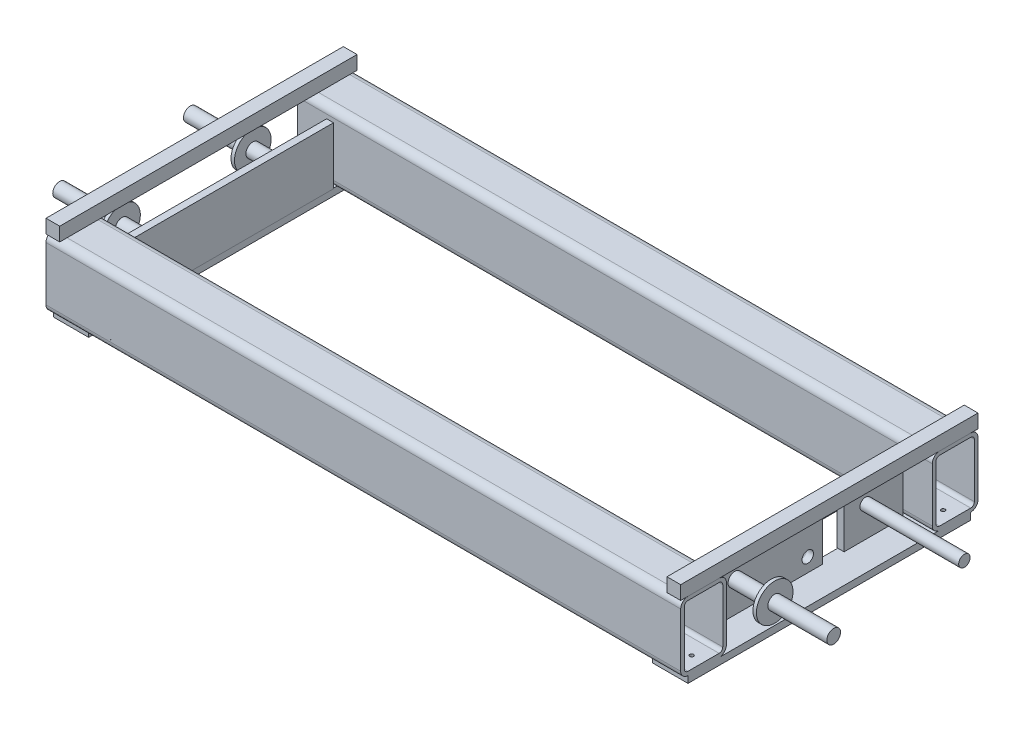
SolidWorks part; units mm, degrees
material "Plain Carbon Steel"
ref_plane "Front Plane" through (0, 0, 0) normal (0, 0, 1) x (1, 0, 0)
ref_plane "Top Plane" through (0, 0, 0) normal (0, 1, 0) x (1, 0, 0)
ref_plane "Right Plane" through (0, 0, 0) normal (1, 0, 0) x (0, 0, -1)
sketch "Sketch2" plane through (0, 0, 0) normal (0, 1, 0) x (1, 0, 0)
  line L0 (-277.5, 110) -> (-277.5, -110) construction
  line L3 (-277.5, -110) -> (277.5, -110)
  line L5 (-277.5, 110) -> (277.5, 110)
  line L6 (277.5, -110) -> (277.5, 110) construction
  line L7 (0, 110) -> (0, -110) construction
  line L8 (-277.5, 0) -> (277.5, 0) construction
  point P4 (0, 0)
  dimension "D1" = 220
  dimension "D3" = 220
  dimension "D4" = 555
other " C:\\PROGRAM FILES\\SOLIDWORKS CORP\\SOLIDWORKS\\LANG\\ENGLISH\\WELDMENT PROFILES\\BSI\\TUBE RECTANGULAR - IS MISSING(1)"
ref_plane "Plane1" through (-277.5, 0, 110) normal (1, 0, 0) x (0, 0, -1)
sketch "Sketch1" plane through (-277.5, 0, 110) normal (1, 0, 0) x (0, 0, -1)
  line L0 (-13.6, -26.8) -> (13.6, -26.8)
  line L1 (-16.8, -23.6) -> (-16.8, 23.6)
  line L2 (13.6, 26.8) -> (-13.6, 26.8)
  line L3 (16.8, 23.6) -> (16.8, -23.6)
  line L4 (-13.6, -30) -> (13.6, -30)
  line L5 (-20, -23.6) -> (-20, 23.6)
  line L6 (13.6, 30) -> (-13.6, 30)
  line L7 (20, 23.6) -> (20, -23.6)
  line L8 (-20, 0) -> (-16.8, 0) construction
  line L9 (-16.8, 0) -> (16.8, 0) construction
  line L10 (16.8, 0) -> (20, 0) construction
  line L11 (0, 30) -> (0, 26.8) construction
  line L12 (0, 26.8) -> (0, -26.8) construction
  line L13 (0, -26.8) -> (0, -30) construction
  arc A0 (20, 23.6) -> (13.6, 30) centre (13.6, 23.6) ccw
  arc A1 (13.6, -30) -> (20, -23.6) centre (13.6, -23.6) ccw
  arc A2 (-20, -23.6) -> (-13.6, -30) centre (-13.6, -23.6) ccw
  arc A3 (-13.6, 30) -> (-20, 23.6) centre (-13.6, 23.6) ccw
  arc A4 (-13.6, 26.8) -> (-16.8, 23.6) centre (-13.6, 23.6) ccw
  arc A5 (16.8, 23.6) -> (13.6, 26.8) centre (13.6, 23.6) ccw
  arc A6 (13.6, -26.8) -> (16.8, -23.6) centre (13.6, -23.6) ccw
  arc A7 (-16.8, -23.6) -> (-13.6, -26.8) centre (-13.6, -23.6) ccw
  point P6 (20, -30)
  point P33 (-20, -30)
  point P35 (-20, 30)
  point P36 (20, 30)
  point P37 (0, 0)
  point P38 (0, 0)
  dimension "D1" = 6.4
  dimension "Thickness" = 3.2
  dimension "V_leg" = 60
  dimension "H_leg" = 40
sketch "Sketch3" plane through (0, 30, 0) normal (0, 1, 0) x (1, 0, 0)
  line L0 (277.5, 130) -> (-277.5, 130) construction
  line L1 (-277.5, -130) -> (-265.5, -130)
  line L2 (-277.5, -130) -> (-277.5, 130)
  line L3 (-277.5, 130) -> (-265.5, 130)
  line L4 (-265.5, -130) -> (-265.5, 130)
  line L5 (0, 178.4485) -> (0, -196.2826) construction
  line L6 (265.5, -130) -> (265.5, 130)
  line L7 (277.5, 130) -> (265.5, 130)
  line L8 (277.5, -130) -> (277.5, 130)
  line L9 (277.5, -130) -> (265.5, -130)
  dimension "D2" = 12
extrude "Boss-Extrude1" add sketch "Sketch3" along normal blind 12 separate body
sketch "Sketch4" plane through (0, 0, 0) normal (0, 0, 1) x (1, 0, 0)
  line L0 (277.5, -30) -> (-277.5, -30) construction
  line L1 (-252.1, -30) -> (-246.1, -30)
  line L2 (-252.1, -30) -> (-252.1, 20)
  line L3 (-252.1, 20) -> (-246.1, 20)
  line L4 (-246.1, -30) -> (-246.1, 20)
  line L5 (-277.5, 23.6) -> (-277.5, -23.6) construction
  line L6 (0, 63.6899) -> (0, -88.2201) construction
  line L7 (246.1, -30) -> (246.1, 20)
  line L8 (252.1, 20) -> (246.1, 20)
  line L9 (252.1, -30) -> (252.1, 20)
  line L10 (252.1, -30) -> (246.1, -30)
  dimension "D1" = 50
  dimension "D2" = 6
  dimension "D3" = 25.4
  dimension "D4" = 151.9099
extrude "Boss-Extrude2" add sketch "Sketch4" along normal mid plane 180 separate body
sketch "Sketch5" plane through (-252.1, 0, 0) normal (-1, 0, 0) x (0, 0, 1)
  line L0 (90, -30) -> (-90, -30) construction
  line L1 (0, 51.6553) -> (0, -66.7942) construction
  circle A0 centre (-57.15, -3) radius 6
  circle A1 centre (57.15, -3) radius 6
  dimension "D1" = 12
  dimension "D2" = 27
  dimension "D4" = 114.3
  dimension "D3" = 118.4495
extrude "Boss-Extrude3" add sketch "Sketch5" along normal blind 86.36 separate body contours A0
sketch "Sketch7" plane through (-338.46, 0, 0) normal (-1, 0, 0) x (0, 0, 1)
  circle A0 centre (-57.15, -3) radius 16
  circle A1 centre (57.15, -3) radius 16
  circle A2 centre (57.15, -3) radius 6 construction
  circle A3 centre (-57.15, -3) radius 6 construction
  circle A4 centre (57.15, -3) radius 6
  circle A5 centre (-57.15, -3) radius 6
  dimension "D2" = 32
extrude "Boss-Extrude4" add sketch "Sketch7" along normal blind 3 from offset 54.61 separate body offset against normal yes
sketch "Sketch8" plane through (252.1, 0, 0) normal (1, 0, 0) x (0, 0, -1)
  circle A0 centre (-57.15, -3) radius 6
  circle A1 centre (57.15, -3) radius 5
  dimension "D1" = 12
  dimension "D2" = 10
extrude "Boss-Extrude5" add sketch "Sketch8" along normal blind 86.36 separate body
sketch "Sketch9" plane through (338.46, 0, 0) normal (1, 0, 0) x (0, 0, -1)
  circle A0 centre (-57.15, -3) radius 6 construction
  circle A1 centre (-57.15, -3) radius 6
  circle A2 centre (-57.15, -3) radius 16
  dimension "D1" = 32
extrude "Boss-Extrude6" add sketch "Sketch9" along normal blind 3 from offset 54.61 separate body offset against normal yes
sketch "Sketch10" plane through (0, -30, 0) normal (0, -1, 0) x (1, 0, 0)
  line L1 (-277.5, -123.6) -> (-246.5618, -123.6)
  line L2 (-277.5, -123.6) -> (-277.5, 123.6)
  line L3 (-277.5, 123.6) -> (-246.5618, 123.6)
  line L4 (-246.5618, -123.6) -> (-246.5618, 123.6)
  line L5 (277.5, 123.6) -> (-277.5, 123.6) construction
extrude "Boss-Extrude7" add sketch "Sketch10" along normal blind 6 separate body
sketch "Sketch11" plane through (0, -36, 0) normal (0, -1, 0) x (1, 0, 0)
  line L0 (-277.5, -110) -> (277.5, -110) construction
  line L1 (-246.5618, -123.6) -> (-246.5618, 123.6) construction
  line L2 (-277.5, 123.6) -> (-277.5, -123.6) construction
  line L3 (305.25, 0) -> (-305.25, 0) construction
  circle A0 centre (-256.8912, -110) radius 1.65
  circle A1 centre (-267.086, -110) radius 1.65
  circle A2 centre (-267.086, 110) radius 1.65
  circle A3 centre (-256.8912, 110) radius 1.65
  dimension "D1" = 3.3
  dimension "D2" = 3.3
  dimension "D3" = 10.3293
  dimension "D4" = 10.414
extrude "Cut-Extrude1" cut sketch "Sketch11" against normal up to surface (9.2 mm away)
mirror "Mirror1" about plane through (0, 0, 0) normal (1, 0, 0) of "Cut-Extrude1", "Boss-Extrude7"
sketch "Sketch12" plane through (0, 30, 0) normal (0, 1, 0) x (1, 0, 0)
  line L0 (277.5, 64.209) -> (277.5, -114.5446) construction
  line L1 (277.5, -110) -> (277.5, 110) construction
  line L2 (277.5, -130) -> (277.5, 130) construction
  line L3 (283.85, -41.15) -> (283.85, -73.15) construction
  line L4 (252.1, 90) -> (252.1, -90) construction
  dimension "D1" = 6.35
ref_plane "Plane4" through (0, 0, -19.23) normal (0, 0, 1) x (1, 0, 0)
sketch "Sketch18" plane through (0, 0, -19.23) normal (0, 0, 1) x (1, 0, 0)
  line L0 (252.1, 2) -> (252.1, -8) construction
  circle A0 centre (238.004, -3) radius 5
  dimension "D1" = 10
  dimension "D2" = 14.096
extrude "Extrude-Thin1" add sketch "Sketch18" along normal blind 25.4 separate body thin
sketch "Sketch19" plane through (0, 0, -19.23) normal (0, 0, -1) x (-1, 0, 0)
  circle A0 centre (-238.004, -3) radius 5
extrude "Boss-Extrude8" add sketch "Sketch19" along normal blind 131.73 from surface at -25.4 separate body starting at face at (246.004, -3, 6.17)
sketch "Sketch20" plane through (246.1, 0, 0) normal (-1, 0, 0) x (0, 0, 1)
  line L1 (-12.88, 17.7) -> (-0.18, 17.7)
  line L2 (-12.88, 17.7) -> (-12.88, -23.7)
  line L3 (-12.88, -23.7) -> (-0.18, -23.7)
  line L4 (-0.18, 17.7) -> (-0.18, -23.7)
  line L6 (-6.53, 17.7) -> (-6.53, -27.7526) construction
  line L7 (-19.23, 5) -> (-19.23, -11) construction
  line L8 (6.17, 5) -> (-19.23, 5) construction
  line L9 (-19.23, -11) -> (6.17, -11) construction
  dimension "D1" = 12.7
  dimension "D2" = 12.7
  dimension "D3" = 12.7
  dimension "D4" = 6.35
  dimension "D5" = 12.7
  dimension "D6" = 41.4
extrude "Boss-Extrude9" add sketch "Sketch20" along normal blind 3 separate body
sketch "Sketch21" plane through (243.1, 0, 0) normal (-1, 0, 0) x (0, 0, 1)
  line L0 (-12.88, 17.7) -> (-12.88, -23.7) construction
  circle A0 centre (-6.53, 10.8151) radius 5
  circle A1 centre (-6.53, -17.8621) radius 5
  dimension "D1" = 10
  dimension "D2" = 10
  dimension "D3" = 6.35
extrude "Cut-Extrude2" cut sketch "Sketch21" against normal up to surface (9 mm away)
sketch "Sketch22" plane through (246.1, 0, 0) normal (-1, 0, 0) x (0, 0, 1)
  line L0 (90, 20) -> (-90, 20) construction
  line L1 (-38.28, 20) -> (-19.23, 20)
  line L2 (-38.28, 20) -> (-38.28, -30)
  line L3 (-38.28, -30) -> (-19.23, -30)
  line L4 (-19.23, 20) -> (-19.23, -30)
  line L5 (90, -30) -> (-90, -30) construction
  line L6 (-19.23, -25.96) -> (-19.23, 25.96) construction
  dimension "D1" = 19.05
extrude "Cut-Extrude3" cut sketch "Sketch22" against normal up to surface (6 mm away) up to face at (252.1, 10.8151, -1.53)
equation "\"n\"=201.832"
